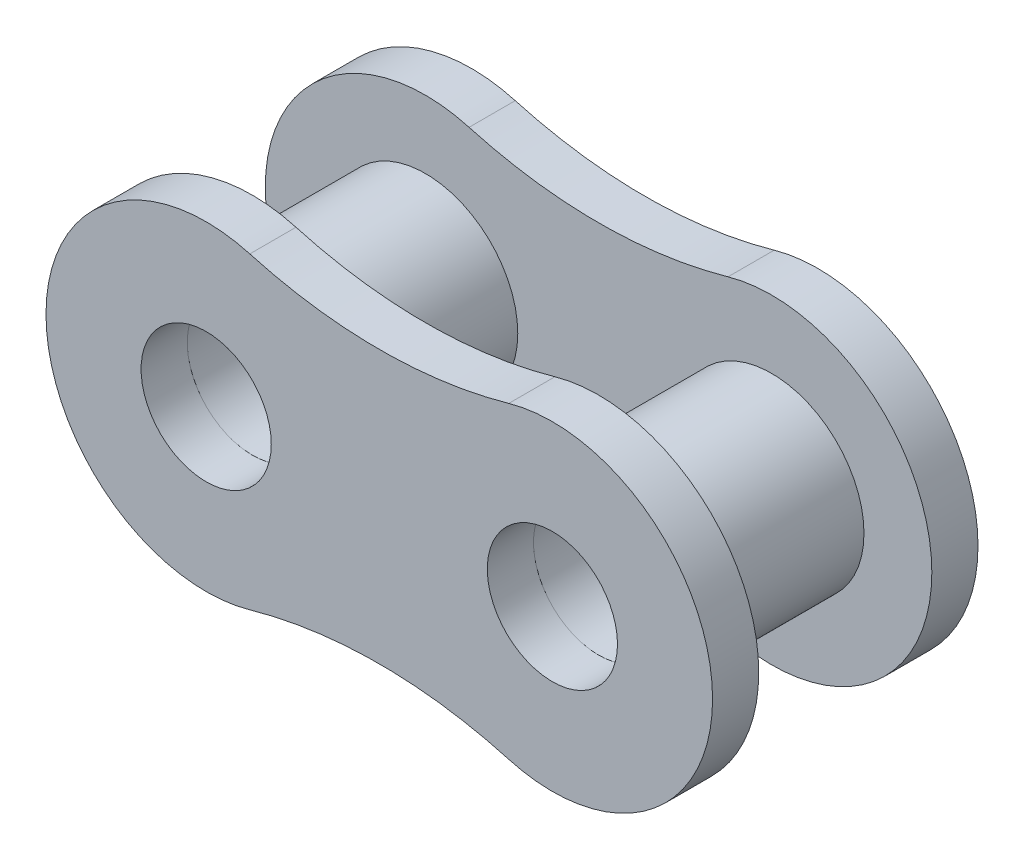
SolidWorks part; units mm, degrees
ref_plane "Front Plane" through (0, 0, 0) normal (0, 0, 1) x (1, 0, 0)
ref_plane "Top Plane" through (0, 0, 0) normal (0, 1, 0) x (1, 0, 0)
ref_plane "Right Plane" through (0, 0, 0) normal (1, 0, 0) x (0, 0, -1)
sketch "Sketch1" plane through (0, 0, 0) normal (0, 0, 1) x (1, 0, 0)
  line L0 (-4.7625, 0) -> (4.7625, 0) construction
  line L1 (-4.7625, 4.4069) -> (-4.7625, -4.4069) construction
  line L2 (0, -3.7459) -> (0, 3.7459) construction
  line L3 (4.7625, -4.4069) -> (4.7625, 4.4069) construction
  circle A0 centre (-4.7625, 0) radius 2.54
  circle A1 centre (4.7625, 0) radius 2.54
  circle A2 centre (-4.7625, 0) radius 1.7907
  circle A3 centre (4.7625, 0) radius 1.7907
  arc A4 (-3.5623, 4.2403) -> (-3.5623, -4.2403) centre (-4.7625, 0) ccw
  arc A5 (3.5623, -4.2403) -> (3.5623, 4.2403) centre (4.7625, 0) ccw
  arc A6 (-3.5623, 4.2403) -> (3.5623, 4.2403) centre (0, 16.8255) ccw
  arc A7 (-3.5623, -4.2403) -> (3.5623, -4.2403) centre (0, -16.8255) cw
  dimension "Roller Dia" = 5.08
  dimension "Pin Dia" = 3.5814
  dimension "Pitch" = 9.525
  dimension "H" = 8.8138
  dimension "D2" = 7.4917
sketch "Sketch2" plane through (0, 0, 0) normal (0, 1, 0) x (1, 0, 0)
  line L0 (0, 2.3813) -> (0, -2.3813) construction
  point P2 (0, -3.6513)
  point P4 (0, 3.6513)
  point P5 (0, 3.7021)
  point P6 (0, 4.9721)
  dimension "W" = 4.7625
  dimension "T" = 1.27
  dimension "D1" = 1.27
  dimension "D2" = 1.27
  dimension "D3" = 0.0508
ref_plane "Plane1" through (0, 0, 2.3813) normal (0, 0, 1) x (1, 0, 0)
ref_plane "Plane2" through (0, 0, -3.7021) normal (0, 0, 1) x (1, 0, 0)
sketch "Sketch4" plane through (0, 0, 0) normal (0, 0, 1) x (1, 0, 0)
  circle A0 centre (-4.7625, 0) radius 2.54 construction
  circle A1 centre (-4.7625, 0) radius 2.54
  circle A2 centre (4.7625, 0) radius 2.54 construction
  circle A3 centre (4.7625, 0) radius 2.54
  circle A4 centre (-4.7625, 0) radius 1.8161
  circle A5 centre (4.7625, 0) radius 1.8161
  dimension "D1" = 3.6322
  dimension "D2" = 3.6322
extrude "Boss-Extrude1" add sketch "Sketch4" along normal mid plane 4.7625
sketch "Sketch5" plane through (0, 0, 2.3813) normal (0, 0, 1) x (1, 0, 0)
  arc A0 (-3.5623, 4.2403) -> (-3.5623, -4.2403) centre (-4.7625, 0) ccw construction
  arc A1 (-3.5623, 4.2403) -> (3.5623, 4.2403) centre (0, 16.8255) ccw construction
  circle A2 centre (-4.7625, 0) radius 1.7907 construction
  arc A3 (3.5623, -4.2403) -> (3.5623, 4.2403) centre (4.7625, 0) ccw construction
  circle A4 centre (4.7625, 0) radius 1.7907 construction
  arc A5 (3.5623, -4.2403) -> (-3.5623, -4.2403) centre (0, -16.8255) ccw construction
  arc A6 (-3.5623, 4.2403) -> (-3.5623, -4.2403) centre (-4.7625, 0) ccw
  arc A7 (-3.5623, 4.2403) -> (3.5623, 4.2403) centre (0, 16.8255) ccw
  circle A8 centre (-4.7625, 0) radius 1.7907
  arc A9 (3.5623, -4.2403) -> (3.5623, 4.2403) centre (4.7625, 0) ccw
  circle A10 centre (4.7625, 0) radius 1.7907
  arc A11 (3.5623, -4.2403) -> (-3.5623, -4.2403) centre (0, -16.8255) ccw
extrude "Boss-Extrude2" add sketch "Sketch5" along normal up to vertex (1.27 mm away) separate body up to point (0, 0, 3.6513)
mirror "Mirror3" about plane through (0, 0, 0) normal (0, 0, 1) of bodies 103
combine bodies "Combine2" operation type add bodies to combine 120 103 102 101
ref_plane "MIDPLANE" through (0, 0, 0) normal (0, 0, 1) x (1, 0, 0)
equation "\"D2@Sketch1\" =\"H@Sketch1\"*.85"
equation "\"D1@Sketch2\" = \"T@Sketch2\""
equation "\"D1@Sketch4\" = \"Pin Dia@Sketch1\"+.002"
equation "\"D2@Sketch4\" = \"D1@Sketch4\""
equation "\"D1@Boss-Extrude1\" = \"W@Sketch2\""
equation "\"D2@Sketch2\" = \"T@Sketch2\""
